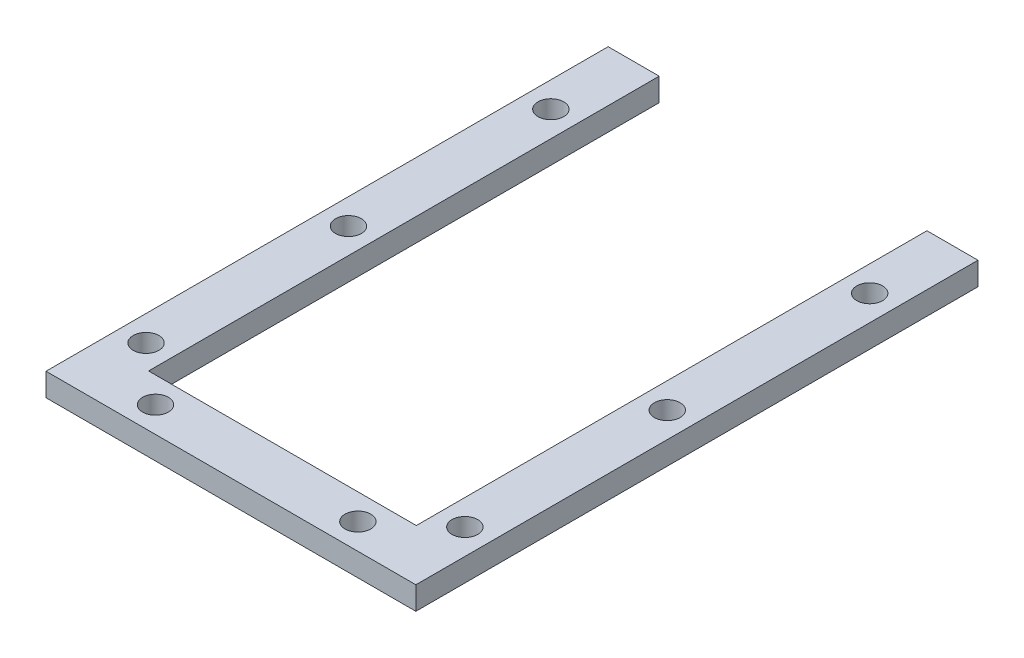
SolidWorks part; units mm, degrees
ref_plane "Front Plane" through (0, 0, 0) normal (0, 0, 1) x (1, 0, 0)
ref_plane "Top Plane" through (0, 0, 0) normal (0, 1, 0) x (1, 0, 0)
ref_plane "Right Plane" through (0, 0, 0) normal (1, 0, 0) x (0, 0, -1)
sketch "Sketch2" plane through (0, 0, 0) normal (0, 1, 0) x (1, 0, 0)
  line L0 (-20.1, 55.5) -> (-20.1, -5.6)
  line L1 (-20.1, -5.6) -> (20.1, -5.6)
  line L2 (20.1, -5.6) -> (20.1, 55.5)
  line L3 (20.1, 55.5) -> (14.55, 55.5)
  line L4 (14.55, 55.5) -> (14.55, 0)
  line L5 (14.55, 0) -> (-14.55, 0)
  line L6 (-14.55, 0) -> (-14.55, 55.5)
  line L7 (-14.55, 55.5) -> (-20.1, 55.5)
  line L8 (0, 0) -> (0, -5.6) construction
  circle A0 centre (-11, -2.8) radius 1.4
  circle A1 centre (11, -2.8) radius 1.4
  circle A2 centre (-17.325, 46.5) radius 1.4
  circle A3 centre (-17.325, 24.5) radius 1.4
  circle A4 centre (-17.325, 2.5) radius 1.4
  circle A5 centre (17.325, 46.5) radius 1.4
  circle A6 centre (17.325, 24.5) radius 1.4
  circle A7 centre (17.325, 2.5) radius 1.4
  point P9 (0, -5.6)
  point P10 (0, 0)
  point P12 (20.1, 24.95)
  point P17 (0, -2.8)
  point P22 (-17.325, 55.5)
  dimension "D5" = 2.8
  dimension "D8" = 2.8
  dimension "D1" = 5.6
  dimension "D2" = 29.1
  dimension "D3" = 40.2
  dimension "D4" = 61.1
  dimension "D6" = 22
  dimension "D7" = 9
  dimension "D9" = 3
extrude "Boss-Extrude1" add sketch "Sketch2" along normal blind 2.5
